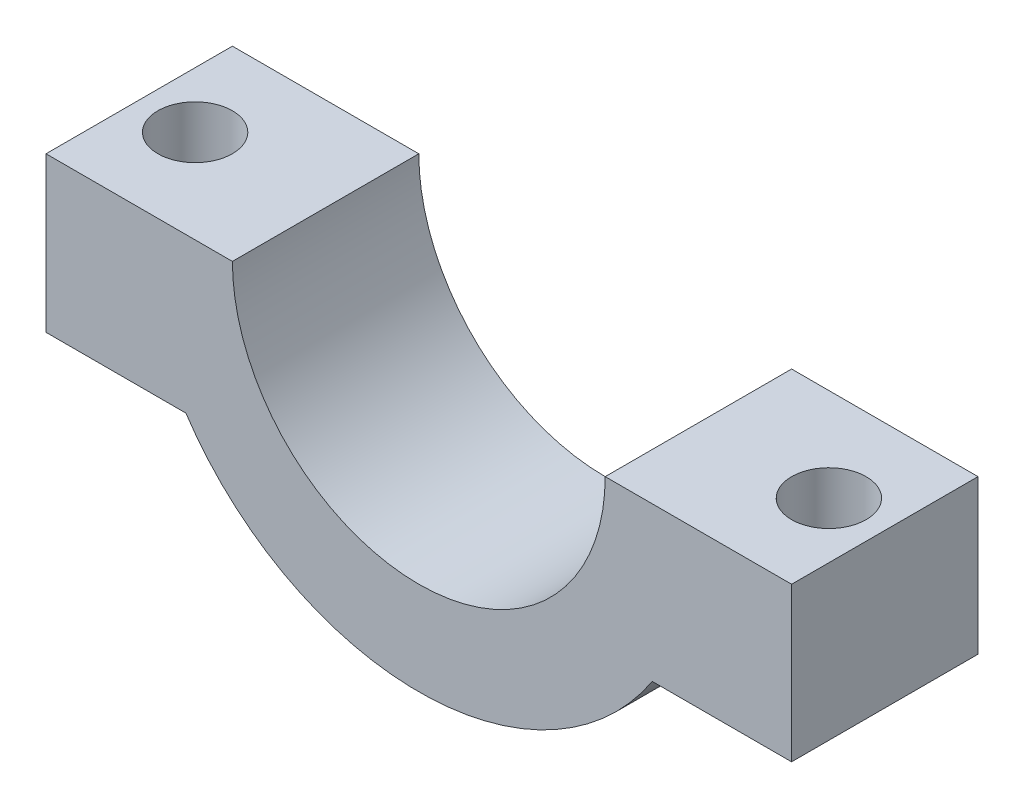
SolidWorks part; units mm, degrees
ref_plane "Front Plane" through (0, 0, 0) normal (0, 0, 1) x (1, 0, 0)
ref_plane "Top Plane" through (0, 0, 0) normal (0, 1, 0) x (1, 0, 0)
ref_plane "Right Plane" through (0, 0, 0) normal (1, 0, 0) x (0, 0, -1)
sketch "Sketch1" plane through (0, 0, 0) normal (0, 0, 1) x (1, 0, 0)
  line L0 (-15, 0) -> (-10, 0)
  line L1 (10, 0) -> (15, 0)
  line L3 (0, 3.0273) -> (0, -16.1633) construction
  line L7 (-15, 0) -> (-20, 0)
  line L8 (-20, 0) -> (-20, -8.297)
  line L9 (-20, -8.297) -> (-12.4964, -8.297)
  line L10 (15, 0) -> (20, 0)
  line L11 (20, 0) -> (20, -8.252)
  line L12 (20, -8.252) -> (12.5261, -8.252)
  arc A0 (-10, 0) -> (10, 0) centre (0, 0) ccw
  arc A3 (-8.5103, -12.3521) -> (8.5103, -12.3521) centre (0, 0) ccw
  arc A4 (-12.4964, -8.297) -> (-8.5103, -12.3521) centre (0, 0) ccw
  arc A5 (8.5103, -12.3521) -> (12.5261, -8.252) centre (0, 0) ccw
  point P16 (0, 0)
extrude "Boss-Extrude1" add sketch "Sketch1" along normal blind 10
sketch "Sketch3" plane through (0, 0, 0) normal (0, 1, 0) x (1, 0, 0)
  line L3 (10, -5) -> (17, -5) construction
  line L6 (10, -10) -> (10, 0) construction
hole_wizard "Ø4.0 (4) Diameter Hole2" positions "Sketch6" profile "Sketch7" hole size "Ø4.0" standard "ANSI Metric"
sketch "Sketch6" plane through (0, 0, 0) normal (0, 1, 0) x (1, 0, 0)
  point P0 (17, -5)
sketch "Sketch7" plane through (17, 0, 5) normal (1, 0, 0) x (0, 0, 1)
  line L0 (0, 0) -> (0, 11.2017)
  line L1 (0, 11.2017) -> (2, 10)
  line L2 (2, 10) -> (2, 0)
  line L5 (2, 0) -> (0, 0)
  line L10 (0, 11.2017) -> (-2, 10) construction
  line L11 (0, -6.35) -> (0, 107.95) construction
  dimension "Hole Dia." = 4
  dimension "Hole Depth" = 10
  dimension "Drill Angle" = 118
mirror "Mirror2" about plane through (0, 0, 0) normal (1, 0, 0) of "Ø4.0 (4) Diameter Hole2"
